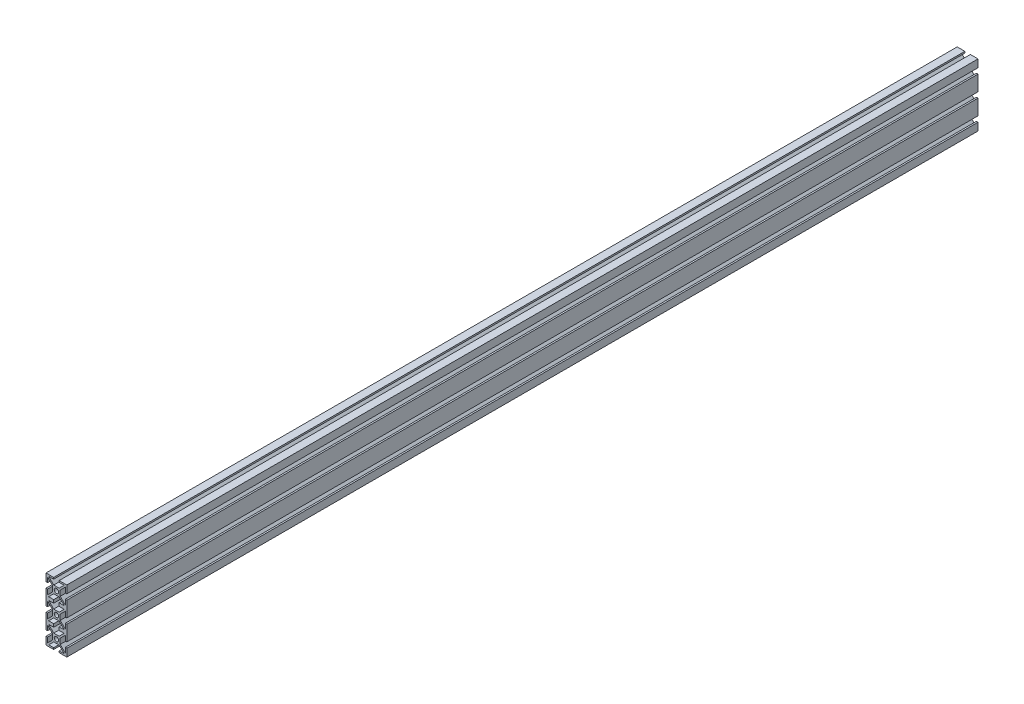
SolidWorks part; units mm, degrees
material "6061-T4 (SS)"
ref_plane "Front Plane" through (0, 0, 0) normal (0, 0, 1) x (1, 0, 0)
ref_plane "Top Plane" through (0, 0, 0) normal (0, 1, 0) x (1, 0, 0)
ref_plane "Right Plane" through (0, 0, 0) normal (1, 0, 0) x (0, 0, -1)
sketch "Sketch1" plane through (0, 0, 0) normal (0, 0, 1) x (1, 0, 0)
  line L0 (0, 20) -> (20, 0) construction
  line L1 (0, 0) -> (20, 0) construction
  line L2 (0, 0) -> (0, 20) construction
  line L3 (0, 20) -> (20, 20) construction
  line L4 (20, 0) -> (20, 20) construction
  line L5 (20, 20) -> (0, 0) construction
  line L6 (18.5, 1.5) -> (18.5, 0) construction
  line L7 (1.5, 1.5) -> (18.5, 1.5) construction
  line L8 (1.5, 1.5) -> (1.5, 18.5) construction
  line L9 (1.5, 18.5) -> (18.5, 18.5) construction
  line L10 (18.5, 1.5) -> (18.5, 18.5) construction
  line L11 (18.5, 1.5) -> (20, 1.5) construction
  line L12 (6.345, 12.5943) -> (1.5, 17.4393)
  line L13 (13.655, 6.345) -> (6.345, 6.345) construction
  line L14 (13.655, 6.345) -> (13.655, 13.655) construction
  line L15 (13.655, 13.655) -> (6.345, 13.655) construction
  line L16 (6.345, 6.345) -> (6.345, 13.655) construction
  line L17 (7.4057, 13.655) -> (2.5607, 18.5)
  line L18 (2.5607, 18.5) -> (2.0303, 17.9697) construction
  line L19 (2.0303, 17.9697) -> (1.5, 17.4393) construction
  line L20 (6.345, 7.4057) -> (6.345, 12.5943)
  line L21 (12.5943, 13.655) -> (17.4393, 18.5)
  line L22 (17.4393, 18.5) -> (17.9697, 17.9697) construction
  line L23 (17.9697, 17.9697) -> (18.5, 17.4393) construction
  line L24 (18.5, 17.4393) -> (13.655, 12.5943)
  line L25 (13.655, 7.4057) -> (18.5, 2.5607)
  line L26 (18.5, 2.5607) -> (17.9697, 2.0303) construction
  line L27 (17.4393, 1.5) -> (12.5943, 6.345)
  line L28 (7.4057, 6.345) -> (2.5607, 1.5)
  line L29 (17.9697, 2.0303) -> (17.4393, 1.5) construction
  line L30 (1.5, 2.5607) -> (6.345, 7.4057)
  line L31 (2.5607, 1.5) -> (2.0303, 2.0303) construction
  line L32 (2.0303, 2.0303) -> (1.5, 2.5607) construction
  line L33 (7.4057, 13.655) -> (12.5943, 13.655)
  line L34 (13.655, 12.5943) -> (13.655, 7.4057)
  line L36 (12.5943, 6.345) -> (7.4057, 6.345)
  line L37 (0, 10) -> (1.5, 10) construction
  line L38 (0.75, 12.63) -> (0.75, 10) construction
  line L39 (0.75, 10) -> (0.75, 7.37) construction
  line L40 (1.5, 12.63) -> (0, 12.63)
  line L41 (1.5, 7.37) -> (0, 7.37)
  line L42 (10, 1.5) -> (10, 0) construction
  line L43 (10, 0.75) -> (12.63, 0.75) construction
  line L44 (10, 0.75) -> (7.37, 0.75) construction
  line L45 (12.63, 0) -> (12.63, 1.5)
  line L46 (7.37, 1.5) -> (7.37, 0)
  line L47 (18.5, 12.63) -> (20, 12.63)
  line L48 (18.5, 7.37) -> (20, 7.37)
  line L49 (7.37, 20) -> (7.37, 18.5)
  line L50 (12.63, 20) -> (12.63, 18.5)
  line L51 (2.5607, 1.5) -> (7.37, 1.5)
  line L52 (12.63, 1.5) -> (17.4393, 1.5)
  line L53 (18.5, 7.37) -> (18.5, 2.5607)
  line L54 (18.5, 12.63) -> (18.5, 17.4393)
  line L55 (17.4393, 18.5) -> (12.63, 18.5)
  line L56 (7.37, 18.5) -> (2.5607, 18.5)
  line L57 (1.5, 17.4393) -> (1.5, 12.63)
  line L58 (1.5, 7.37) -> (1.5, 2.5607)
  line L59 (7.37, 0) -> (0, 0)
  line L60 (0, 0) -> (0, 7.37)
  line L61 (0, 12.63) -> (0, 20)
  line L62 (0, 20) -> (7.37, 20)
  line L63 (12.63, 20) -> (20, 20)
  line L64 (20, 20) -> (20, 12.63)
  line L65 (20, 7.37) -> (20, 0)
  line L66 (20, 0) -> (12.63, 0)
  circle A0 centre (10, 10) radius 2.095
  dimension "D2" = 4.19
  dimension "D6" = 5.26
  dimension "D1" = 20
  dimension "D3" = 1.5
  dimension "D4" = 3.655
  dimension "D5" = 1.5
extrude "Boss-Extrude1" add sketch "Sketch1" along normal blind 875
pattern_linear "LPattern1" count 3 spacing 20 along (0, -1, 0) of "Boss-Extrude1"
